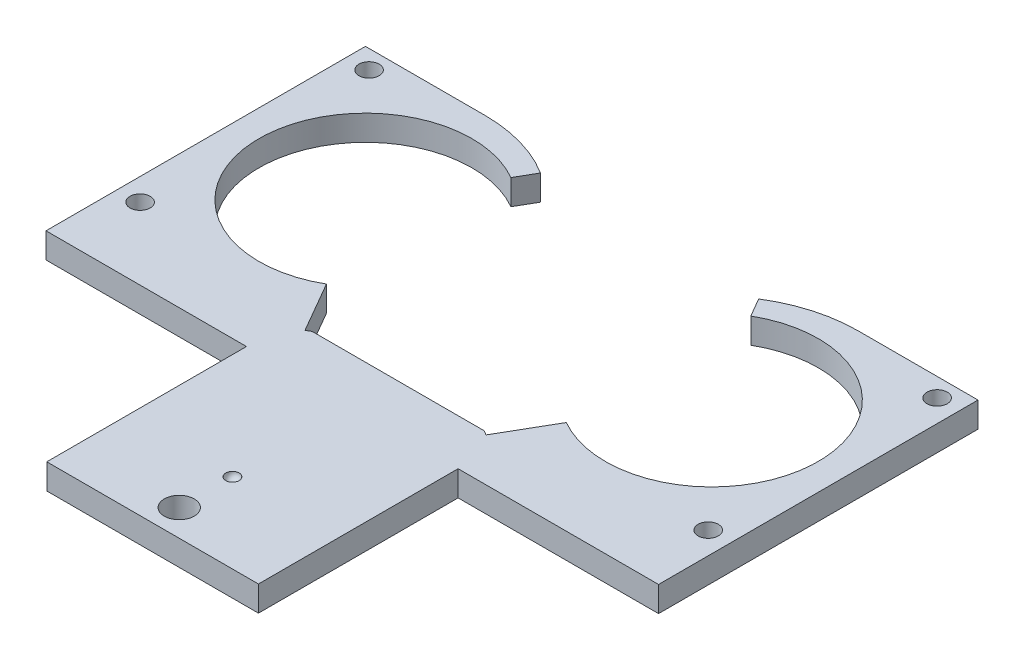
SolidWorks part; units mm, degrees
ref_plane "Front" through (0, 0, 0) normal (0, 0, 1) x (1, 0, 0)
ref_plane "Top" through (0, 0, 0) normal (0, 1, 0) x (1, 0, 0)
ref_plane "Right" through (0, 0, 0) normal (1, 0, 0) x (0, 0, -1)
sketch "Croquis1" plane through (0, 0, 0) normal (0, 1, 0) x (1, 0, 0)
  line L0 (16.4201, 3.45) -> (29.5999, 3.45)
  line L1 (0, -356.9204) -> (0, 17489.0978) construction
  line L2 (10, -986.0798) -> (10, 49013.9202) construction
  line L3 (-356.9204, 3) -> (17489.0978, 3) construction
  line L4 (0, 0) -> (0, 24)
  line L5 (0, 24) -> (9, 24)
  line L6 (20, 12) -> (20, 13)
  line L7 (-697.1068, -693.1068) -> (34658.2323, 34662.2323) construction
  line L8 (8.4, 3.45) -> (11.6, 3.45) construction
  line L9 (8.4, 3.45) -> (8.4, 1.25) construction
  line L10 (8.4, 1.25) -> (11.6, 1.25) construction
  line L11 (11.6, 3.45) -> (11.6, 1.25) construction
  line L12 (8.4, 3.45) -> (11.6, 1.25) construction
  line L13 (8.4, 1.25) -> (11.6, 3.45) construction
  line L14 (-685.9891, 732.5482) -> (34101.0787, -35182.0716) construction
  line L15 (-990, 14) -> (49010, 14) construction
  line L16 (6.5, -986.0798) -> (6.5, 49013.9202) construction
  line L17 (4.6, 3.45) -> (4.6, 1.25) construction
  line L18 (4.6, 1.25) -> (1.4, 1.25) construction
  line L19 (1.4, 3.45) -> (1.4, 1.25) construction
  line L20 (4.6, 3.45) -> (1.4, 3.45) construction
  line L21 (23.01, -356.9204) -> (23.01, 17489.0978) construction
  line L22 (37.62, 3.45) -> (37.62, 1.25) construction
  line L23 (37.62, 1.25) -> (34.42, 1.25) construction
  line L24 (34.42, 3.45) -> (34.42, 1.25) construction
  line L25 (37.62, 3.45) -> (34.42, 3.45) construction
  line L26 (44.62, 3.45) -> (44.62, 1.25) construction
  line L27 (41.42, 1.25) -> (44.62, 1.25) construction
  line L28 (41.42, 3.45) -> (41.42, 1.25) construction
  line L29 (41.42, 3.45) -> (44.62, 3.45) construction
  line L31 (46.02, 24) -> (37.02, 24)
  line L32 (46.02, 0) -> (46.02, 24)
  line L33 (26.02, 12) -> (26.02, 13)
  line L34 (-659.7674, -704.2477) -> (34129.605, 35208.1396) construction
  line L35 (0, 0) -> (15.06, 0)
  line L36 (15.06, -15) -> (30.96, -15)
  line L37 (15.06, -15) -> (15.06, 0)
  line L38 (30.96, -15) -> (30.96, 0)
  line L40 (30.96, 0) -> (46.02, 0)
  circle A0 centre (10, 14) radius 8
  circle A1 centre (1.67, 22.6) radius 0.76
  circle A2 centre (1.67, 5.4) radius 0.76
  arc A3 (20, 13) -> (9, 24) centre (9, 13) ccw
  arc A4 (20, 12) -> (16.4201, 3.45) centre (8, 12) cw
  circle A5 centre (36.02, 14) radius 8
  arc A6 (26.02, 12) -> (29.5999, 3.45) centre (38.02, 12) ccw
  arc A7 (26.02, 13) -> (37.02, 24) centre (37.02, 13) cw
  circle A8 centre (44.35, 5.4) radius 0.76
  circle A9 centre (44.35, 22.6) radius 0.76
  point P9 (10, 2.35)
  point P65 (23.01, -15)
  point P72 (23.01, 3.45)
  dimension "D1" = 16
  dimension "D3" = 10
  dimension "D5" = 10
  dimension "D9" = 1.52
  dimension "D10" = 1.67
  dimension "D11" = 1.4
  dimension "D12" = 11
  dimension "D13" = 12
  dimension "D14" = 3.5
  dimension "D4" = 24
  dimension "D6" = 3.2
  dimension "D7" = 2.2
  dimension "D8" = 15.9
  dimension "D15" = 23.01
  dimension "D17" = 15
extrude "Saliente-Extruir1" add sketch "Croquis1" along normal blind 1.9
sketch "Croquis2" plane through (0, 1.9, 0) normal (0, 1, 0) x (1, 0, 0)
  line L0 (10, -986) -> (10, 49014) construction
  line L1 (-990, 14) -> (49010, 14) construction
  line L2 (-482.4039, -838.8685) -> (24517.5961, 42462.4017) construction
  line L3 (-472.9629, 850.5163) -> (24527.0371, -42450.7539) construction
  line L4 (16.2085, 24.7534) -> (14, 20.9282)
  line L5 (14, 7.0718) -> (16.2085, 3.2466)
  line L6 (7.53, -1000) -> (7.53, 49000) construction
  line L7 (0, 0) -> (15.06, 0) construction
  line L8 (23.01, -996.55) -> (23.01, 49003.45) construction
  line L10 (32.02, 7.0718) -> (29.8115, 3.2466)
  line L11 (29.8115, 24.7534) -> (32.02, 20.9282)
  line L12 (29.5999, 3.45) -> (16.4201, 3.45) construction
  circle A0 centre (10, 14) radius 8 construction
  arc A1 (14, 20.9282) -> (14, 7.0718) centre (10, 14) cw
  arc A2 (16.2085, 3.2466) -> (16.2085, 24.7534) centre (10, 14) ccw
  arc A3 (16.4201, 3.45) -> (20, 12) centre (8, 12) ccw construction
  arc A4 (32.02, 20.9282) -> (32.02, 7.0718) centre (36.02, 14) ccw
  arc A5 (29.8115, 3.2466) -> (29.8115, 24.7534) centre (36.02, 14) cw
  point P23 (7.53, 0)
  point P36 (23.01, 3.45)
  dimension "D1" = 30
extrude "Cortar-Extruir1" cut sketch "Croquis2" against normal blind 10
sketch "Croquis3" plane through (0, 0, 0) normal (0, 1, 0) x (1, 0, 0)
  line L1 (0, 24) -> (9, 24)
  line L2 (0, 24) -> (0, 25.5)
  line L3 (0, 25.5) -> (9, 25.5)
  line L4 (9, 24) -> (9, 25.5)
  dimension "D1" = 9
  dimension "D2" = 1.5
extrude "Saliente-Extruir2" [suppressed] add sketch "Croquis3" along normal blind 4
ref_plane "Plano1" through (0, 0, 9) normal (0, 0, 1) x (1, 0, 0)
sketch "Croquis4" plane through (0, 0, 9) normal (0, 0, 1) x (1, 0, 0)
  line L0 (-976.99, 1.9) -> (49023.01, 1.9) construction
  line L1 (15.06, 1.9) -> (30.96, 1.9) construction
  line L2 (23.01, -998.1) -> (23.01, 49001.9) construction
  line L3 (22.51, 1.9) -> (23.51, 1.9)
  arc A0 (22.51, 1.9) -> (23.51, 1.9) centre (23.01, 1.9) ccw
  point P5 (23.01, 1.9)
  dimension "D1" = 1
revolve "Cortar-Revolución1" cut sketch "Croquis4" angle 360 about L0
sketch "Croquis5" plane through (0, 1.9, 0) normal (0, 1, 0) x (1, 0, 0)
  line L0 (23.01, -996.55) -> (23.01, 49003.45) construction
  line L2 (15.06, -15) -> (30.96, -15) construction
  line L3 (29.4719, 3.45) -> (16.5481, 3.45) construction
  circle A0 centre (23.01, -13) radius 1.125
  point P12 (23.01, 3.45)
  dimension "D1" = 2.25
  dimension "D2" = 2
extrude "Cortar-Extruir2" cut sketch "Croquis5" against normal through all
